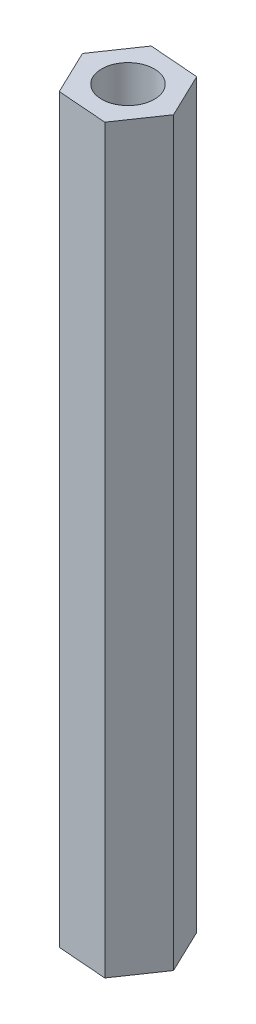
SolidWorks part; units mm, degrees
ref_plane "前视基准面" through (0, 0, 0) normal (0, 0, 1) x (1, 0, 0)
ref_plane "上视基准面" through (0, 0, 0) normal (0, 1, 0) x (1, 0, 0)
ref_plane "右视基准面" through (0, 0, 0) normal (1, 0, 0) x (0, 0, -1)
other "Configuration Table"
sketch "草图1" plane through (0, 0, 0) normal (0, 1, 0) x (1, 0, 0)
  line L1 (1.2984, -2.7069) -> (2.9935, -0.229)
  line L2 (2.9935, -0.229) -> (1.695, 2.4779)
  line L3 (1.695, 2.4779) -> (-1.2984, 2.7069)
  line L4 (-1.2984, 2.7069) -> (-2.9935, 0.229)
  line L5 (-2.9935, 0.229) -> (-1.695, -2.4779)
  line L6 (-1.695, -2.4779) -> (1.2984, -2.7069)
  circle A0 centre (0, 0) radius 2.6 construction
  circle A1 centre (0, 0) radius 1.6
  dimension "D1" = 5.2
  dimension "D2" = 3.2
extrude "凸台-拉伸1" add sketch "草图1" along normal blind 45
